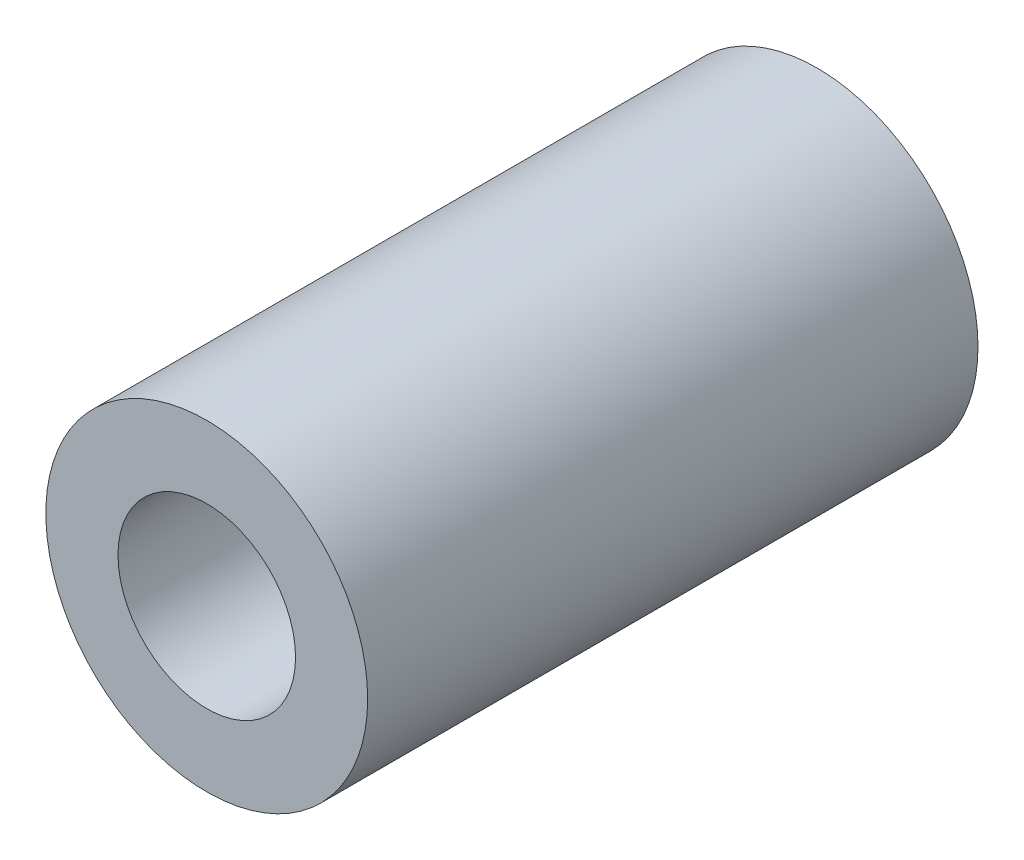
SolidWorks part; units mm, degrees
ref_plane "Płaszczyzna przednia" through (0, 0, 0) normal (0, 0, 1) x (1, 0, 0)
ref_plane "Płaszczyzna górna" through (0, 0, 0) normal (0, 1, 0) x (1, 0, 0)
ref_plane "Płaszczyzna prawa" through (0, 0, 0) normal (1, 0, 0) x (0, 0, -1)
sketch "Szkic1" plane through (0, 0, 0) normal (0, 0, 1) x (1, 0, 0)
  circle A0 centre (0, 0) radius 2.9
  dimension "D1" = 5.8
extrude "Dodanie-wyciągnięcie1" add sketch "Szkic1" along normal blind 11 contours A0
sketch "Szkic2" plane through (0, 0, 11) normal (0, 0, 1) x (1, 0, 0)
  circle A0 centre (0, 0) radius 1.6
  dimension "D1" = 3.2
extrude "Wytnij-wyciągnięcie1" cut sketch "Szkic2" against normal through all contours A0
